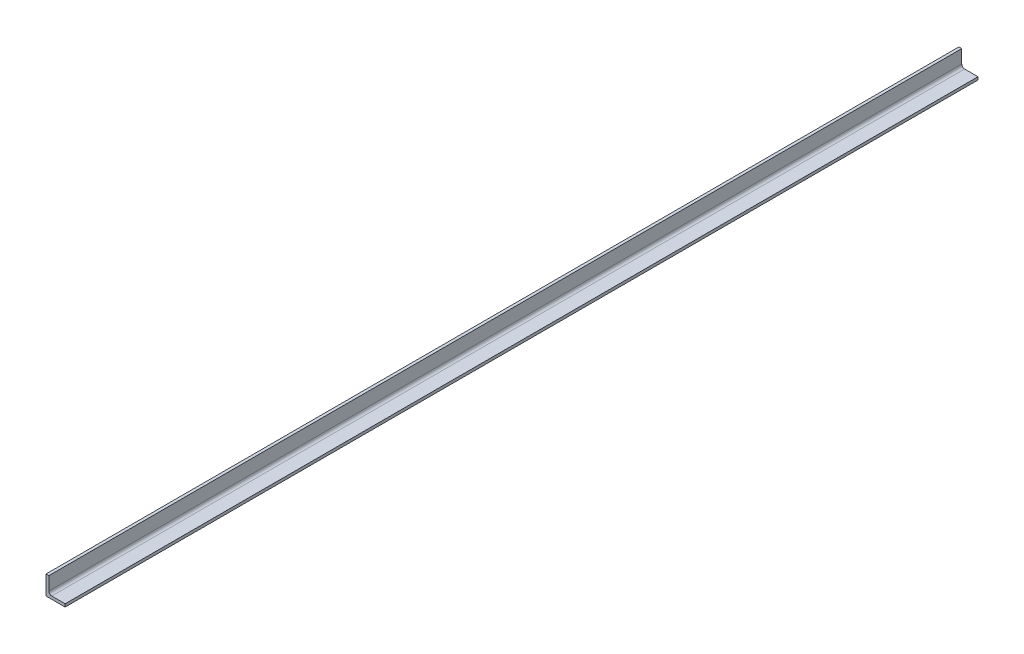
SolidWorks part; units mm, degrees
ref_plane "Plan de face" through (0, 0, 0) normal (0, 0, 1) x (1, 0, 0)
ref_plane "Plan de dessus" through (0, 0, 0) normal (0, 1, 0) x (1, 0, 0)
ref_plane "Plan de droite" through (0, 0, 0) normal (1, 0, 0) x (0, 0, -1)
sketch "Esquisse1" plane through (0, 0, 0) normal (0, 0, 1) x (1, 0, 0)
  line L0 (0, 0) -> (0, 20)
  line L1 (0, 20) -> (3, 20)
  line L2 (3, 20) -> (3, 6)
  line L3 (6, 3) -> (20, 3)
  line L4 (20, 3) -> (20, 0)
  line L5 (20, 0) -> (0, 0)
  arc A0 (3, 6) -> (6, 3) centre (6, 6) ccw
  dimension "D5" = 3
  dimension "D1" = 20
  dimension "D2" = 20
  dimension "D3" = 3
  dimension "D4" = 3
extrude "Boss.-Extru.1" add sketch "Esquisse1" along normal blind 955
